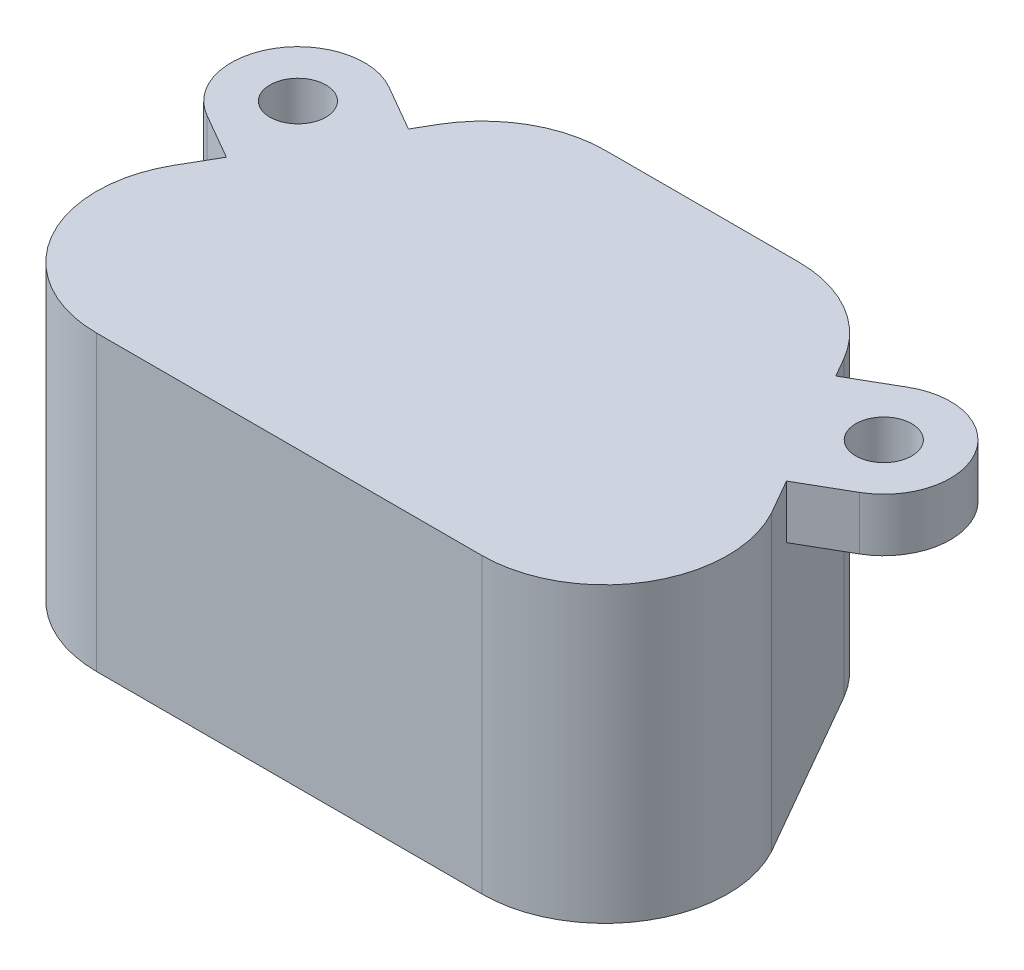
SolidWorks part; units mm, degrees
ref_plane "Front Plane" through (0, 0, 0) normal (0, 0, 1) x (1, 0, 0)
ref_plane "Top Plane" through (0, 0, 0) normal (0, 1, 0) x (1, 0, 0)
ref_plane "Right Plane" through (0, 0, 0) normal (1, 0, 0) x (0, 0, -1)
sketch "Sketch1" plane through (0, 0, 0) normal (0, 1, 0) x (1, 0, 0)
  line L0 (-66.4492, -19.2368) -> (-54.2896, 1.8196) construction
  line L5 (-47.4217, 6.4932) -> (-32.9217, 6.4932)
  line L6 (-13.0797, -20.8119) -> (-32.5543, 13.1499) construction
  line L11 (-54.6454, -20.463) -> (-25.7454, -20.463)
  line L12 (-53.6238, 2.9725) -> (-60.945, -9.7053)
  line L13 (-26.6666, 2.8823) -> (-19.3841, -9.8177)
  line L14 (-47.4217, 8.4932) -> (-32.9217, 8.4932)
  line L15 (-24.933, 3.8797) -> (-17.6364, -8.8449)
  line L16 (-54.6454, -22.463) -> (-25.7454, -22.463)
  line L17 (-55.349, 3.9845) -> (-62.6828, -8.7152)
  line L18 (-64.7173, -20.237) -> (-52.5577, 0.8194) construction
  line L19 (-11.3447, -19.817) -> (-30.8193, 14.1448) construction
  arc A0 (-19.3841, -9.8177) -> (-25.7454, -20.463) centre (-25.7454, -13.2396) cw
  arc A1 (-60.945, -9.7053) -> (-54.6454, -20.463) centre (-54.6454, -13.2396) ccw
  arc A2 (-47.4217, 6.4932) -> (-53.6238, 2.9725) centre (-47.4217, -0.7302) ccw
  arc A3 (-32.9217, 6.4932) -> (-26.6666, 2.8823) centre (-32.9217, -0.7302) cw
  arc A4 (-32.9217, 8.4932) -> (-24.933, 3.8797) centre (-32.9217, -0.7302) cw
  arc A5 (-17.6364, -8.8449) -> (-25.7454, -22.463) centre (-25.7454, -13.2396) cw
  arc A6 (-62.6828, -8.7152) -> (-54.6454, -22.463) centre (-54.6454, -13.2396) ccw
  arc A7 (-47.4217, 8.4932) -> (-55.349, 3.9845) centre (-47.4217, -0.7302) ccw
  point P11 (-25.7454, -13.2396)
  dimension "D2" = 7.2233
  dimension "D3" = 2
  dimension "D1" = 14.5
  dimension "D4" = 28.9
  dimension "D5" = 12.7
extrude "Boss-Extrude1" add sketch "Sketch1" along normal blind 20
sketch "Sketch8" plane through (0, 20, 0) normal (0, 1, 0) x (1, 0, 0)
  line L4 (-55.349, 3.9845) -> (-62.6828, -8.7152)
  line L5 (-54.6454, -22.463) -> (-25.7454, -22.463)
  line L6 (-17.6364, -8.8449) -> (-24.933, 3.8797)
  line L7 (-32.9217, 8.4932) -> (-47.4217, 8.4932)
  line L8 (-55.349, 3.9845) -> (-62.6828, -8.7152)
  line L9 (-54.6454, -22.463) -> (-25.7454, -22.463)
  line L10 (-17.6364, -8.8449) -> (-24.933, 3.8797)
  line L11 (-32.9217, 8.4932) -> (-47.4217, 8.4932)
  arc A4 (-47.4217, 8.4932) -> (-55.349, 3.9845) centre (-47.4217, -0.7302) ccw
  arc A5 (-62.6828, -8.7152) -> (-54.6454, -22.463) centre (-54.6454, -13.2396) ccw
  arc A6 (-25.7454, -22.463) -> (-17.6364, -8.8449) centre (-25.7454, -13.2396) ccw
  arc A7 (-24.933, 3.8797) -> (-32.9217, 8.4932) centre (-32.9217, -0.7302) ccw
  arc A8 (-47.4217, 8.4932) -> (-55.349, 3.9845) centre (-47.4217, -0.7302) ccw
  arc A9 (-62.6828, -8.7152) -> (-54.6454, -22.463) centre (-54.6454, -13.2396) ccw
  arc A10 (-25.7454, -22.463) -> (-17.6364, -8.8449) centre (-25.7454, -13.2396) ccw
  arc A11 (-24.933, 3.8797) -> (-32.9217, 8.4932) centre (-32.9217, -0.7302) ccw
  dimension "D1" = 0
extrude "Boss-Extrude4" add sketch "Sketch8" along normal blind 2
sketch "Sketch9" plane through (0, 22, 0) normal (0, 1, 0) x (1, 0, 0)
  line L0 (-40.1717, 8.4932) -> (-40.1954, -22.463) construction
  line L1 (-32.9217, 8.4932) -> (-47.4217, 8.4932) construction
  line L2 (-54.6454, -22.463) -> (-25.7454, -22.463) construction
  line L3 (-59.6741, 4.4935) -> (-56.2102, 2.4932)
  line L4 (-55.349, 3.9845) -> (-62.6828, -8.7152) construction
  line L5 (-64.6749, -4.1663) -> (-61.211, -6.1666)
  line L6 (-61.211, -6.1666) -> (-56.2102, 2.4932)
  line L7 (-64.6749, -4.1663) -> (-59.6741, 4.4935) construction
  line L8 (-15.6879, -4.2038) -> (-20.6754, 4.4636) construction
  line L9 (-19.1549, -6.1988) -> (-24.1424, 2.4686)
  line L10 (-15.6879, -4.2038) -> (-19.1549, -6.1988)
  line L11 (-20.6754, 4.4636) -> (-24.1424, 2.4686)
  arc A0 (-59.6741, 4.4935) -> (-64.6749, -4.1663) centre (-62.1745, 0.1636) ccw
  circle A2 centre (-62.1745, 0.1636) radius 2.1
  circle A3 centre (-18.1817, 0.1299) radius 2.1
  arc A4 (-20.6754, 4.4636) -> (-15.6879, -4.2038) centre (-18.1817, 0.1299) cw
  dimension "D1" = 5
  dimension "D4" = 4.2
  dimension "D2" = 4
  dimension "D3" = 6
extrude "Boss-Extrude5" add sketch "Sketch9" against normal blind 4
